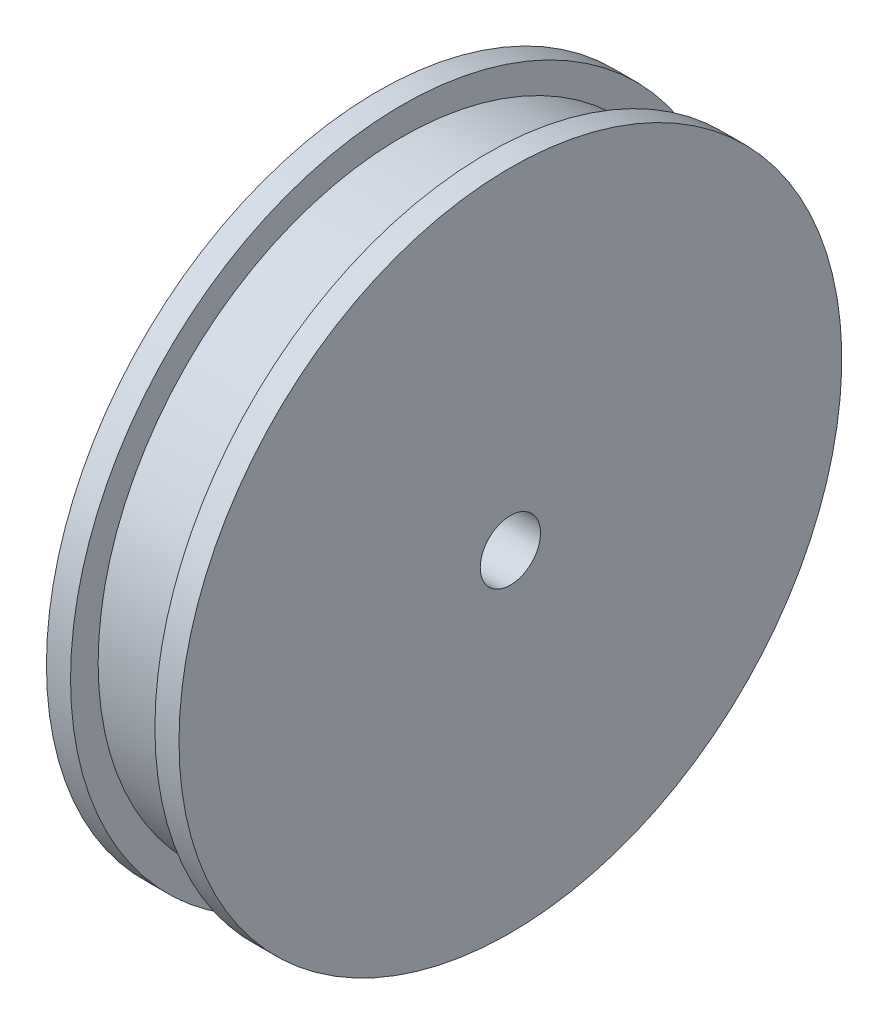
SolidWorks part; units mm, degrees
ref_plane "Front Plane" through (0, 0, 0) normal (0, 0, 1) x (1, 0, 0)
ref_plane "Top Plane" through (0, 0, 0) normal (0, 1, 0) x (1, 0, 0)
ref_plane "Right Plane" through (0, 0, 0) normal (1, 0, 0) x (0, 0, -1)
sketch "Sketch1" plane through (0, 0, 0) normal (0, 1, 0) x (1, 0, 0)
  line L0 (0, 0) -> (31.2957, 0) construction
  line L1 (0, -2.5) -> (0, -15)
  line L2 (0, -15) -> (7, -15)
  line L3 (7, -15) -> (7, -27.5)
  line L4 (7, -27.5) -> (9, -27.5)
  line L5 (9, -27.5) -> (9, -25.21)
  line L6 (9, -25.21) -> (16, -25.21)
  line L7 (16, -25.21) -> (16, -27.5)
  line L8 (16, -27.5) -> (18, -27.5)
  line L9 (18, -27.5) -> (18, -2.5)
  line L10 (0, -2.5) -> (18, -2.5)
  point P11 (0, 0)
  point P14 (0, 0)
  dimension "D1" = 15
  dimension "D2" = 2.5
  dimension "D3" = 7
  dimension "D4" = 18
  dimension "D5" = 2
  dimension "D6" = 2
  dimension "D7" = 27.5
  dimension "D8" = 25.21
revolve "Revolve1" add sketch "Sketch1" angle 360 about L0
equation "\"extrustion OD\" = 30"
equation "\"D1@Sketch1\" = \"extrustion OD\" / 2"
equation "\"lip\"=2"
equation "\"D6@Sketch1\"=\"lip\""
equation "\"D5@Sketch1\"=\"lip\""
equation "\"geared section\"=7"
equation "\"D3@Sketch1\"=\"geared section\""
equation "\"gear OD\" = 50.42"
equation "\"D8@Sketch1\" = \"gear OD\" / 2"
equation "\"OD\" = 55"
equation "\"D7@Sketch1\" = \"OD\" / 2"
equation "\"M5\"= 5"
